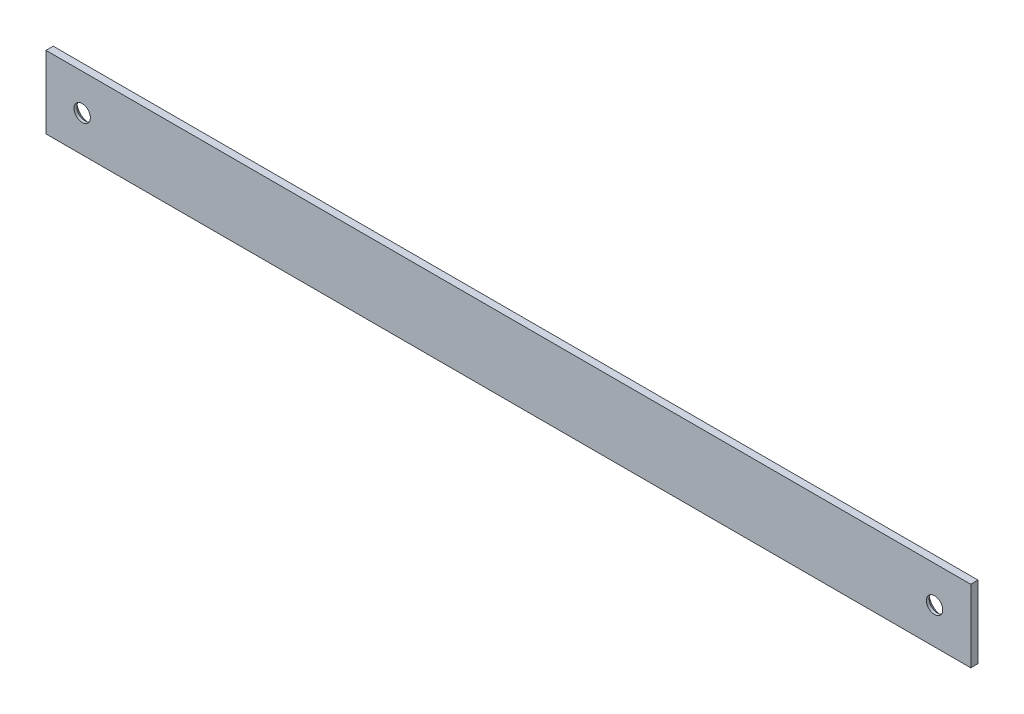
SolidWorks part; units mm, degrees
ref_plane "Front Plane" through (0, 0, 0) normal (0, 0, 1) x (1, 0, 0)
ref_plane "Top Plane" through (0, 0, 0) normal (0, 1, 0) x (1, 0, 0)
ref_plane "Right Plane" through (0, 0, 0) normal (1, 0, 0) x (0, 0, -1)
sketch "Sketch3" plane through (0, 0, 0) normal (0, 0, 1) x (1, 0, 0)
  line L1 (-121.6872, 9.525) -> (121.6872, 9.525)
  line L2 (-121.6872, 9.525) -> (-121.6872, -9.525)
  line L3 (-121.6872, -9.525) -> (121.6872, -9.525)
  line L4 (121.6872, 9.525) -> (121.6872, -9.525)
  point P1 (-121.6872, 0)
  point P4 (0, 9.525)
  dimension "D2" = 19.05
  dimension "D3" = 243.3743
extrude "Boss-Extrude1" add sketch "Sketch3" along normal blind 1.905
sketch "Sketch4" plane through (0, 0, 0) normal (0, 0, -1) x (-1, 0, 0)
  line L1 (-112.1622, 0) -> (-112.1622, -9.525) construction
  line L4 (112.1622, -9.525) -> (112.1622, 0) construction
  line L5 (121.6872, -9.525) -> (-121.6872, -9.525) construction
  line L7 (121.6872, 9.525) -> (121.6872, -9.525) construction
  line L8 (112.1622, 0) -> (121.6872, 0) construction
  line L10 (-112.1622, 0) -> (-121.6872, 0) construction
  line L11 (-121.6872, -9.525) -> (-121.6872, 9.525) construction
  line L13 (121.6872, -9.525) -> (-121.6872, -9.525) construction
  point P11 (-112.1622, 0)
  point P22 (121.6872, 0)
  point P25 (112.1622, 0)
hole_wizard "#6 Clearance Hole1" positions "Sketch4" profile "Sketch5" hole size "#6" standard "ANSI Inch" end condition up to next
sketch "Sketch5" plane through (-112.1622, 0, 0) normal (1, 0, 0) x (0, 1, 0)
  line L0 (0, 0) -> (0, 1.905)
  line L1 (0, 1.905) -> (2.1526, 1.905)
  line L2 (2.1526, 1.905) -> (2.1526, 1.1748)
  line L3 (2.1526, 1.1748) -> (3.3274, 0)
  line L5 (3.3274, 0) -> (0, 0)
  line L6 (-2.1526, 1.1747) -> (-3.3274, 0) construction
  line L11 (0, -6.35) -> (0, 107.95) construction
  dimension "Thru Hole Dia." = 4.3053
  dimension "Thru Hole Depth" = 1.905
  dimension "Near C'Sink Dia." = 6.6548
  dimension "Near C'Sink Angle" = 90
